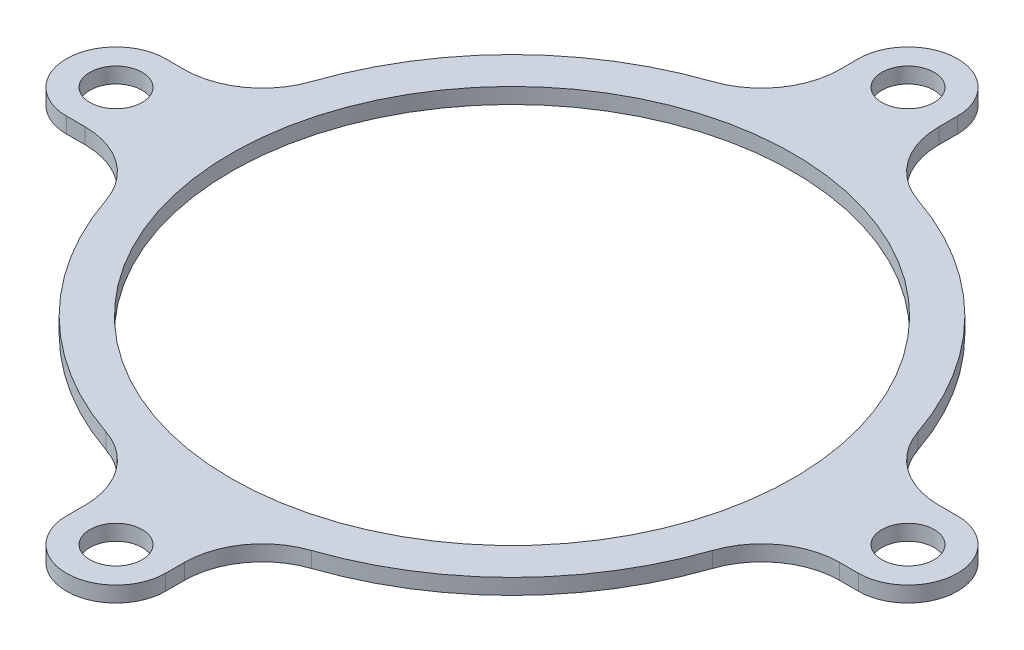
SolidWorks part; units mm, degrees
ref_plane "Front Plane" through (0, 0, 0) normal (0, 0, 1) x (1, 0, 0)
ref_plane "Top Plane" through (0, 0, 0) normal (0, 1, 0) x (1, 0, 0)
ref_plane "Right Plane" through (0, 0, 0) normal (1, 0, 0) x (0, 0, -1)
sketch "Sketch1" plane through (0, 0, 0) normal (0, 1, 0) x (1, 0, 0)
  circle A0 centre (0, 0) radius 36
  circle A1 centre (0, 0) radius 41
  dimension "D1" = 72
  dimension "outerDiam" = 82
extrude "Boss-Extrude1" add sketch "Sketch1" along normal mid plane 2
sketch "Sketch2" plane through (0, 1, 0) normal (0, 1, 0) x (1, 0, 0)
  line L0 (0, 0) -> (0, 38.8704) construction
  line L1 (-6.35, 48.3082) -> (-6.35, 50.7)
  line L2 (6.35, 50.7) -> (6.35, 48.3082)
  arc A0 (-6.35, 50.7) -> (6.35, 50.7) centre (0, 50.7) cw
  arc A1 (6.35, 48.3082) -> (13.1441, 38.836) centre (16.35, 48.3082) ccw
  circle A2 centre (0, 0) radius 41 construction
  arc A3 (-6.35, 48.3082) -> (-13.1441, 38.836) centre (-16.35, 48.3082) cw
  arc A4 (13.1441, 38.836) -> (-13.1441, 38.836) centre (0, 0) ccw
  circle A5 centre (0, 0) radius 50.7 construction
  circle A6 centre (0, 50.7) radius 3.35
  dimension "supportsDiam" = 101.4
  dimension "rodDiam" = 6.7
  dimension "D3" = 3
  dimension "D4" = 10
extrude "Boss-Extrude2" add sketch "Sketch2" against normal up to surface (2 mm away) up to face at (0, -1, 41)
pattern_circular "CirPattern1" count 4 over 360 about axis through (0, 0, 0) along (0, 1, 0) of "Boss-Extrude2"
